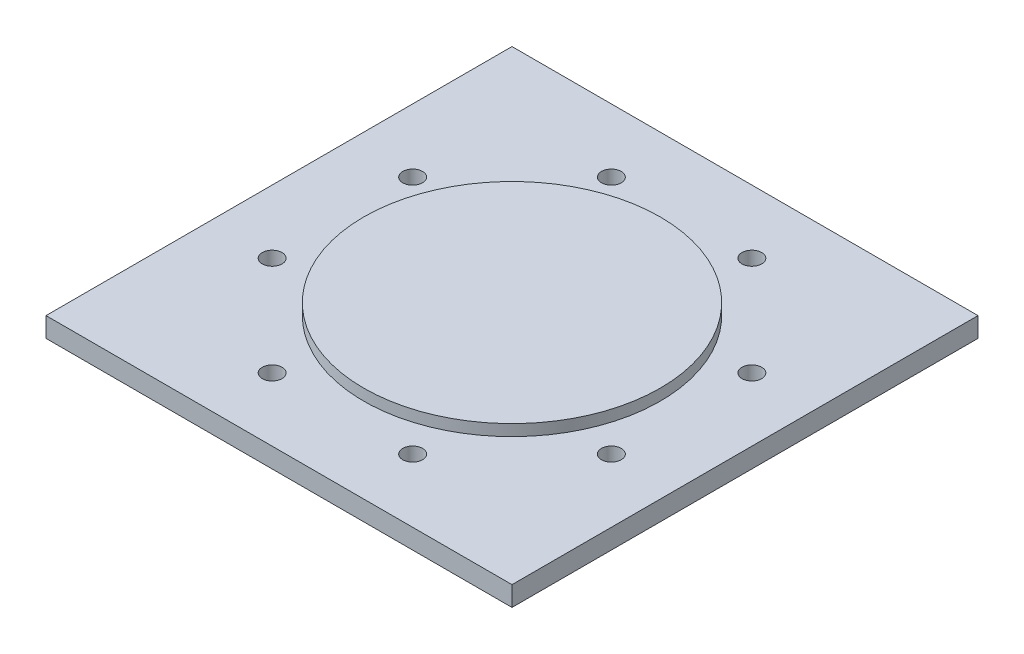
SolidWorks part; units mm, degrees
ref_plane "前视基准面" through (0, 0, 0) normal (0, 0, 1) x (1, 0, 0)
ref_plane "上视基准面" through (0, 0, 0) normal (0, 1, 0) x (1, 0, 0)
ref_plane "右视基准面" through (0, 0, 0) normal (1, 0, 0) x (0, 0, -1)
other "Configuration Table"
sketch "01_Base_Profile" plane through (0, 0, 0) normal (0, 1, 0) x (1, 0, 0)
  line L1 (-165, -165) -> (165, -165)
  line L2 (-165, -165) -> (-165, 165)
  line L3 (-165, 165) -> (165, 165)
  line L4 (165, -165) -> (165, 165)
  line L5 (-165, -165) -> (165, 165) construction
  line L6 (-165, 165) -> (165, -165) construction
  circle A0 centre (120.1043, 49.7488) radius 7
  circle A1 centre (49.7488, 120.1043) radius 7
  circle A2 centre (-49.7488, 120.1043) radius 7
  circle A3 centre (-120.1043, 49.7488) radius 7
  circle A4 centre (-120.1043, -49.7488) radius 7
  circle A5 centre (-49.7488, -120.1043) radius 7
  circle A6 centre (49.7488, -120.1043) radius 7
  circle A7 centre (120.1043, -49.7488) radius 7
  circle A8 centre (49.7488, 49.7488) radius 5.2486
  circle A9 centre (-49.7488, 49.7488) radius 5.7514
  circle A10 centre (-49.7488, -49.7488) radius 5.7514
  circle A11 centre (49.7488, -49.7488) radius 5.2486
  point P0 (0, 0)
extrude "01_Base_Extrude" add sketch "01_Base_Profile" along normal blind 14
sketch "02_Boss_Profile" plane through (0, 0, 0) normal (0, 1, 0) x (1, 0, 0)
  circle A0 centre (0, 0) radius 105
extrude "02_Reinforcement_Boss" add sketch "02_Boss_Profile" along normal blind 22
